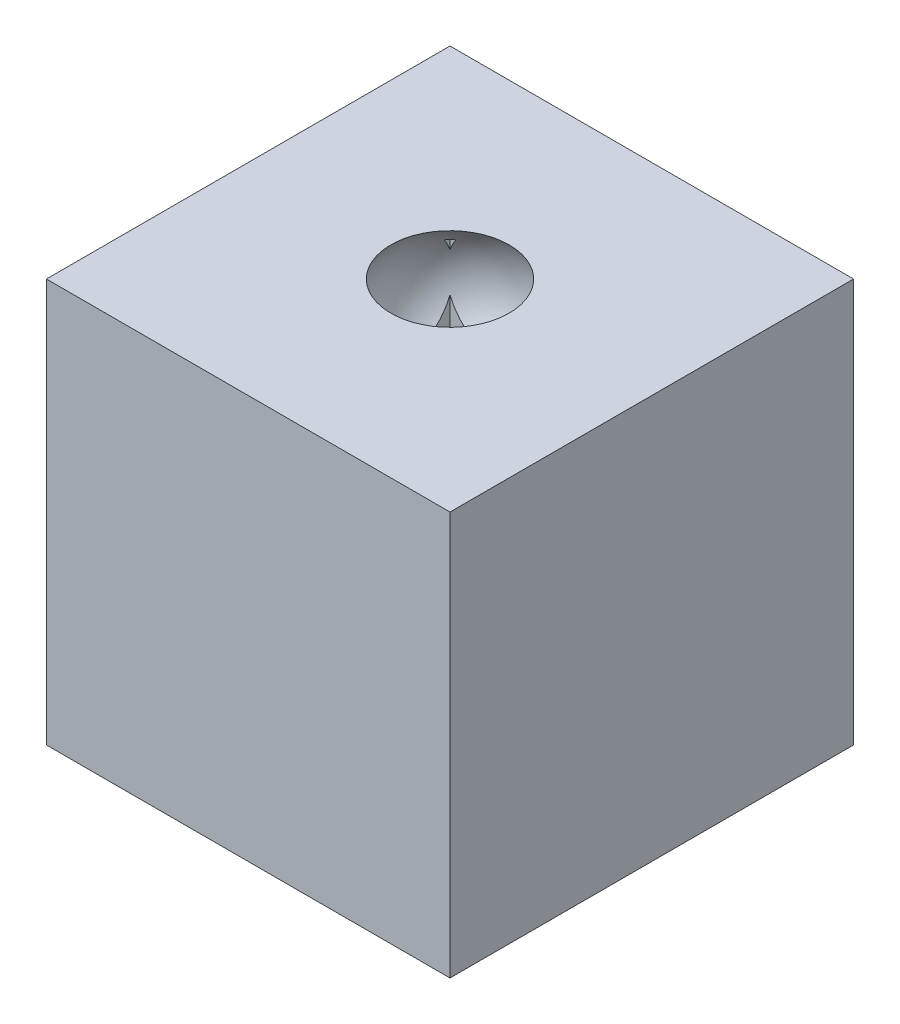
SolidWorks part; units mm, degrees
ref_plane "Front Plane" through (0, 0, 0) normal (0, 0, 1) x (1, 0, 0)
ref_plane "Top Plane" through (0, 0, 0) normal (0, 1, 0) x (1, 0, 0)
ref_plane "Right Plane" through (0, 0, 0) normal (1, 0, 0) x (0, 0, -1)
sketch "Sketch1" plane through (0, 0, 0) normal (0, 1, 0) x (1, 0, 0)
  line L1 (-38.1, -38.1) -> (38.1, -38.1)
  line L2 (-38.1, -38.1) -> (-38.1, 38.1)
  line L3 (-38.1, 38.1) -> (38.1, 38.1)
  line L4 (38.1, -38.1) -> (38.1, 38.1)
  line L5 (-38.1, -38.1) -> (38.1, 38.1) construction
  line L6 (-38.1, 38.1) -> (38.1, -38.1) construction
  point P0 (0, 0)
  dimension "D1" = 76.2
  dimension "D2" = 76.2
extrude "main body" add sketch "Sketch1" along normal blind 76.2
sketch "Sketch5" plane through (0, 0, 0) normal (0, 0, 1) x (1, 0, 0)
  line L0 (0, -906.782) -> (0, 49093.218) construction
  line L1 (0, 81.788) -> (0, 53.848)
  line L2 (-38.1, 76.2) -> (38.1, 76.2) construction
  arc A0 (0, 81.788) -> (0, 53.848) centre (0, 67.818) cw
  dimension "D1" = 8.382
revolve "trackball hole" cut sketch "Sketch5" angle 360 about L0
sketch "Sketch6" plane through (0, 0, 0) normal (0, -1, 0) x (1, 0, 0)
  line L1 (-25.4, -16.51) -> (25.4, -16.51)
  line L2 (-25.4, -16.51) -> (-25.4, 16.51)
  line L3 (-25.4, 16.51) -> (25.4, 16.51)
  line L4 (25.4, -16.51) -> (25.4, 16.51)
  line L5 (-25.4, -16.51) -> (25.4, 16.51) construction
  line L6 (-25.4, 16.51) -> (25.4, -16.51) construction
  point P0 (0, 0)
  dimension "D1" = 50.8
  dimension "D2" = 33.02
extrude "camera base" add sketch "Sketch6" along normal blind 2.54
shell "shell" thickness 2.54
sketch "Sketch13" plane through (0, 0, 0) normal (0, -1, 0) x (1, 0, 0)
  line L0 (-25.4, 16.51) -> (-25.4, -16.51) construction
  line L1 (25.4, -16.51) -> (25.4, 16.51) construction
  circle A0 centre (-25.4, 0) radius 1.905
  circle A1 centre (25.4, 0) radius 1.905
  dimension "D1" = 3.81
  dimension "D2" = 3.81
extrude "screw mounts" add sketch "Sketch13" along normal up to surface (2.54 mm away) up to face at (0, -2.54, 0)
hole_wizard "#4-40 Tapped Hole1" positions "Sketch15" profile "Sketch14" tap size "#4-40" standard "ANSI Inch"
sketch "Sketch15" plane through (0, 0, 0) normal (0, -1, 0) x (-1, 0, 0)
  point P0 (25.4, 0)
  point P2 (-25.4, 0)
  dimension "D1" = 50.8
sketch "Sketch14" plane through (-25.4, 0, 0) normal (1, 0, 0) x (0, 0, -1)
  line L0 (0, 0) -> (0, 74.3382)
  line L1 (0, 74.3382) -> (1.1303, 73.659)
  line L2 (1.1303, 73.659) -> (1.1303, 0)
  line L5 (1.1303, 0) -> (0, 0)
  line L10 (0, 74.3382) -> (-1.1303, 73.659) construction
  line L11 (0, -6.35) -> (0, 107.95) construction
  dimension "Tap Drill Dia." = 2.2606
  dimension "Tap Drill Depth" = 73.659
  dimension "Drill Angle" = 118
sketch "Sketch16" plane through (0, 0, 0) normal (0, 1, 0) x (1, 0, 0)
  line L1 (-9.525, 9.525) -> (9.525, 9.525)
  line L2 (-9.525, 9.525) -> (-9.525, -9.525)
  line L3 (-9.525, -9.525) -> (9.525, -9.525)
  line L4 (9.525, 9.525) -> (9.525, -9.525)
  line L5 (-9.525, 9.525) -> (9.525, -9.525) construction
  line L6 (-9.525, -9.525) -> (9.525, 9.525) construction
  point P0 (0, 0)
  dimension "D1" = 19.05
  dimension "D2" = 19.05
extrude "check out the bottom" cut sketch "Sketch16" along normal up to surface (73.66 mm away) up to face at (0, 73.66, -15.4419)
